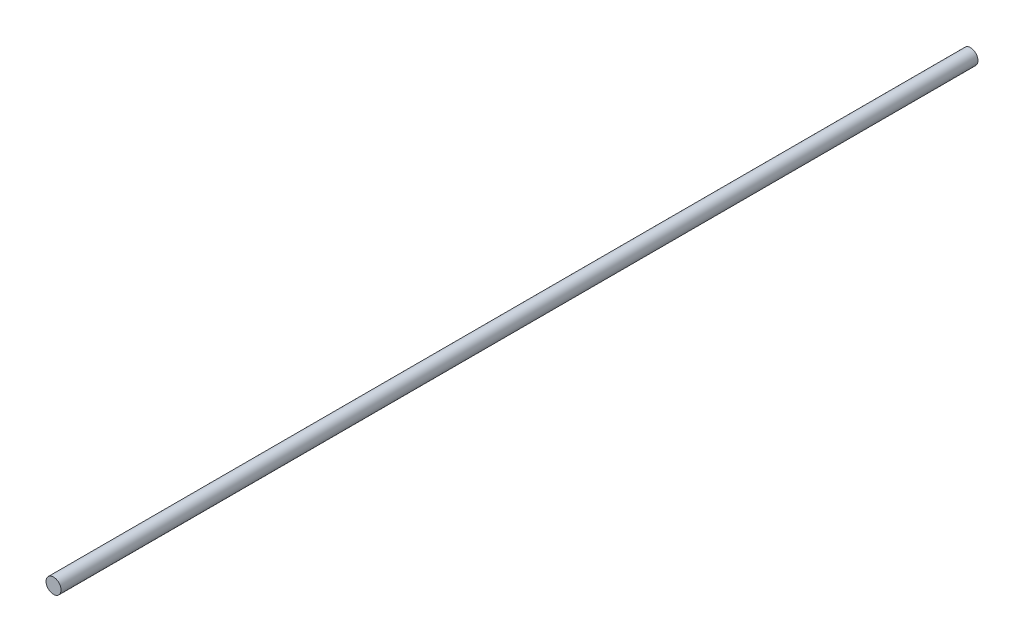
SolidWorks part; units mm, degrees
ref_plane "Front Plane" through (0, 0, 0) normal (0, 0, 1) x (1, 0, 0)
ref_plane "Top Plane" through (0, 0, 0) normal (0, 1, 0) x (1, 0, 0)
ref_plane "Right Plane" through (0, 0, 0) normal (1, 0, 0) x (0, 0, -1)
sketch "Sketch1" plane through (0, 0, 0) normal (0, 0, 1) x (1, 0, 0)
  circle A0 centre (0, 0) radius 10
extrude "Boss-Extrude1" add sketch "Sketch1" along normal blind 1219.2
